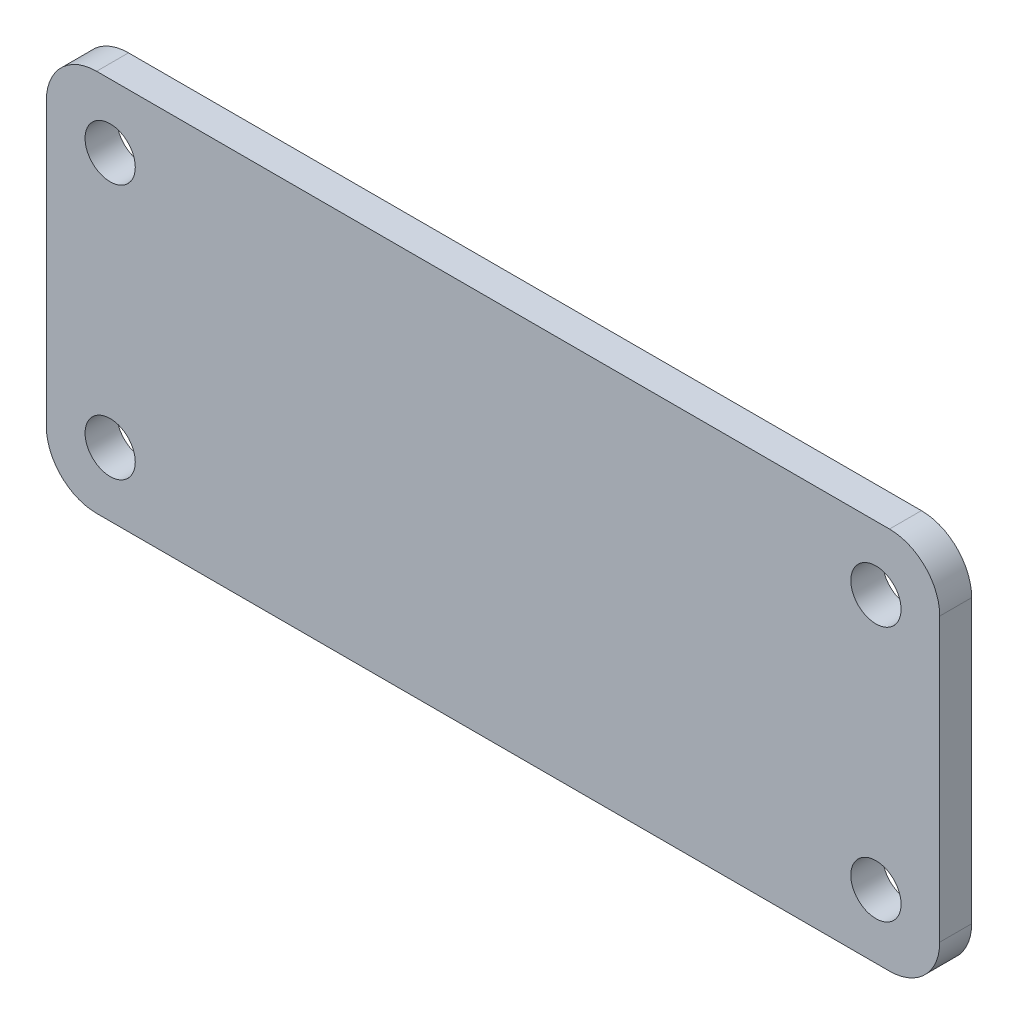
SolidWorks part; units mm, degrees
ref_plane "Front Plane" through (0, 0, 0) normal (0, 0, 1) x (1, 0, 0)
ref_plane "Top Plane" through (0, 0, 0) normal (0, 1, 0) x (1, 0, 0)
ref_plane "Right Plane" through (0, 0, 0) normal (1, 0, 0) x (0, 0, -1)
sketch "Sketch1" plane through (0, 0, 0) normal (0, 0, 1) x (1, 0, 0)
  line L1 (5, 0) -> (83.9, 0)
  line L2 (0, 5) -> (0, 33.1)
  line L3 (5, 38.1) -> (83.9, 38.1)
  line L4 (88.9, 5) -> (88.9, 33.1)
  circle A0 centre (6.35, 31.75) radius 2.5
  circle A1 centre (82.55, 31.75) radius 2.5
  circle A2 centre (82.55, 6.35) radius 2.5
  circle A3 centre (6.35, 6.35) radius 2.5
  arc A4 (0, 33.1) -> (5, 38.1) centre (5, 33.1) cw
  arc A5 (5, 0) -> (0, 5) centre (5, 5) cw
  arc A6 (88.9, 33.1) -> (83.9, 38.1) centre (83.9, 33.1) ccw
  arc A7 (83.9, 0) -> (88.9, 5) centre (83.9, 5) ccw
  point P17 (0, 0)
  dimension "D3" = 5
  dimension "D8" = 5
  dimension "D9" = 5
  dimension "D10" = 5
  dimension "D11" = 5
  dimension "D1" = 38.1
  dimension "D2" = 88.9
  dimension "D4" = 6.35
  dimension "D5" = 6.35
  dimension "D6" = 2
  dimension "D7" = 2
extrude "Boss-Extrude1" add sketch "Sketch1" along normal blind 3.175
